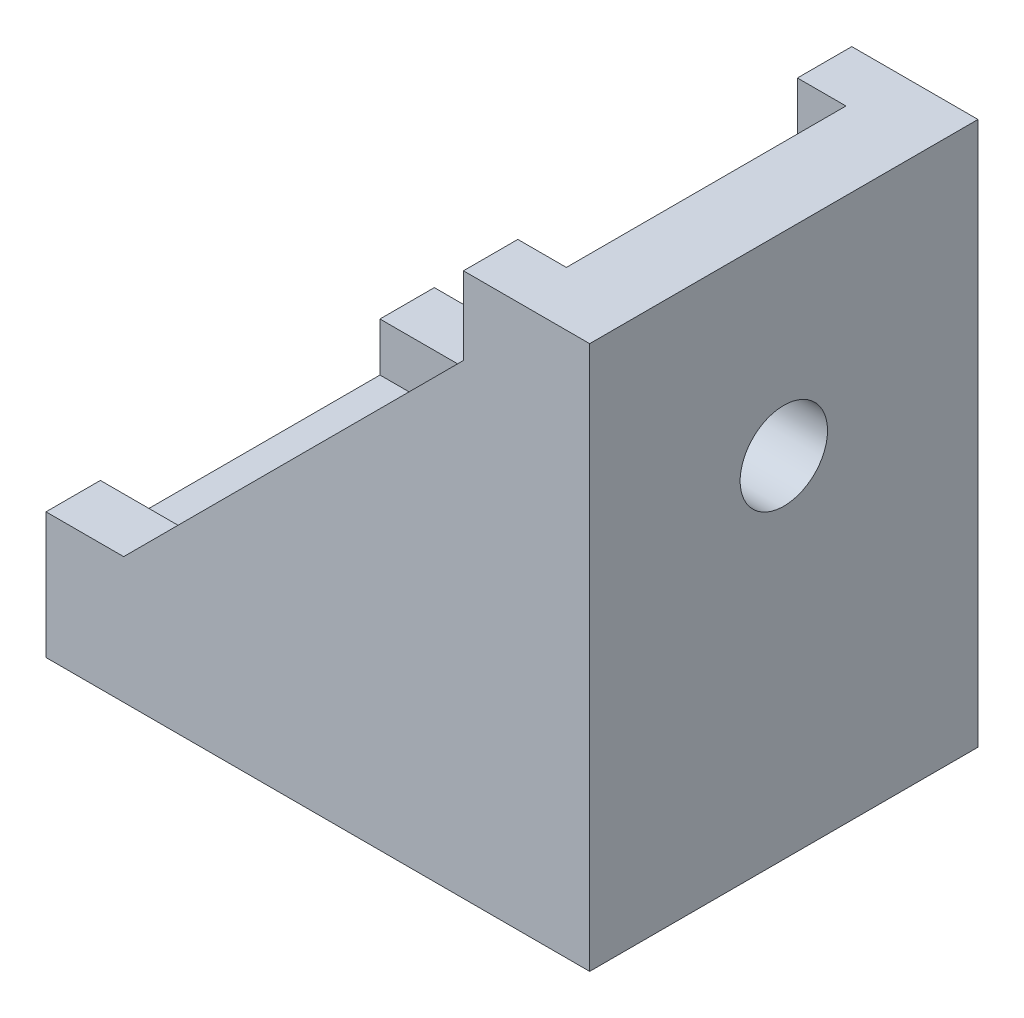
SolidWorks part; units mm, degrees
ref_plane "前视基准面" through (0, 0, 0) normal (0, 0, 1) x (1, 0, 0)
ref_plane "上视基准面" through (0, 0, 0) normal (0, 1, 0) x (1, 0, 0)
ref_plane "右视基准面" through (0, 0, 0) normal (1, 0, 0) x (0, 0, -1)
sketch "草图1" plane through (0, 0, 0) normal (0, 0, 1) x (1, 0, 0)
  line L1 (0, 0) -> (28, 0)
  line L2 (0, 0) -> (0, 28)
  line L3 (0, 28) -> (28, 28)
  line L4 (28, 0) -> (28, 28)
  dimension "D1" = 28
  dimension "D2" = 28
extrude "凸台-拉伸1" add sketch "草图1" along normal blind 20
sketch "草图2" plane through (0, 0, 20) normal (0, 0, 1) x (1, 0, 0)
  line L0 (21.5, 28) -> (21.5, 24)
  line L1 (28, 28) -> (0, 28) construction
  line L2 (21.5, 24) -> (4, 6.5)
  line L3 (4, 6.5) -> (0, 6.5)
  line L4 (0, 28) -> (0, 0) construction
  line L5 (28, 0) -> (28, 28) construction
  line L6 (0, 0) -> (28, 0) construction
  line L7 (21.5, 28) -> (0, 28)
  line L8 (0, 28) -> (0, 6.5)
  dimension "D1" = 6.5
  dimension "D2" = 6.5
  dimension "D3" = 135
  dimension "D4" = 24
extrude "切除-拉伸1" cut sketch "草图2" against normal blind 20
sketch "草图3" plane through (0, 28, 0) normal (0, 1, 0) x (1, 0, 0)
  line L0 (0, 0) -> (0, -20) construction
  line L1 (0, -2.8) -> (24, -2.8)
  line L2 (0, -2.8) -> (0, -17.2)
  line L3 (0, -17.2) -> (24, -17.2)
  line L4 (24, -2.8) -> (24, -17.2)
  line L5 (4, 0) -> (21.5, 0) construction
  line L6 (4, -20) -> (21.5, -20) construction
  line L7 (28, -20) -> (28, 0) construction
  dimension "D1" = 2.8
  dimension "D2" = 2.8
  dimension "D3" = 4
extrude "切除-拉伸2" cut sketch "草图3" against normal blind 24
sketch "草图4" plane through (0, 0, 0) normal (0, -1, 0) x (1, 0, 0)
  line L0 (28, 20) -> (28, 0) construction
  circle A0 centre (10, 10) radius 2.25
  point P4 (28, 10)
  dimension "D2" = 4.5
  dimension "D1" = 18
extrude "切除-拉伸3" cut sketch "草图4" against normal blind 10
sketch "草图5" plane through (28, 0, 0) normal (1, 0, 0) x (0, 0, -1)
  line L0 (-20, 0) -> (0, 0) construction
  line L1 (-20, 28) -> (0, 28) construction
  circle A0 centre (-10, 18) radius 2.25
  point P6 (-10, 28)
  dimension "D2" = 4.5
  dimension "D1" = 18
extrude "切除-拉伸4" cut sketch "草图5" against normal blind 10
